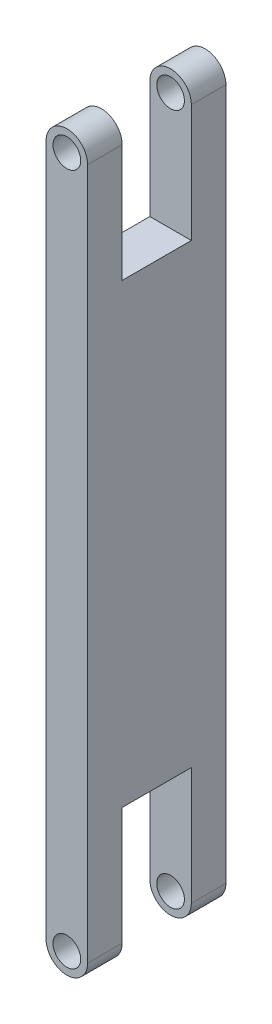
SolidWorks part; units mm, degrees
ref_plane "前视基准面" through (0, 0, 0) normal (0, 0, 1) x (1, 0, 0)
ref_plane "上视基准面" through (0, 0, 0) normal (0, 1, 0) x (1, 0, 0)
ref_plane "右视基准面" through (0, 0, 0) normal (1, 0, 0) x (0, 0, -1)
other "Configuration Table"
sketch "草图1" plane through (0, 0, 0) normal (0, 0, 1) x (1, 0, 0)
  line L0 (0, 0) -> (0, 250) construction
  line L1 (-7.5, 0) -> (-7.5, 250)
  line L2 (7.5, 0) -> (7.5, 250)
  arc A0 (-7.5, 0) -> (7.5, 0) centre (0, 0) ccw
  arc A1 (7.5, 250) -> (-7.5, 250) centre (0, 250) ccw
  point P3 (0, 125)
  dimension "D1" = 7.5
  dimension "D2" = 250
extrude "凸台-拉伸1" add sketch "草图1" along normal blind 50
sketch "草图2" plane through (7.5, 0, 0) normal (1, 0, 0) x (0, 0, -1)
  line L0 (0, 257.5) -> (-50, 257.5) construction
  line L1 (-37.5, 257.5) -> (-12.5, 257.5)
  line L2 (-37.5, 257.5) -> (-37.5, 207.5)
  line L3 (-37.5, 207.5) -> (-12.5, 207.5)
  line L4 (-12.5, 257.5) -> (-12.5, 207.5)
  line L5 (-50, -7.5) -> (0, -7.5) construction
  line L6 (-37.5, -7.5) -> (-12.5, -7.5)
  line L7 (-37.5, -7.5) -> (-37.5, 42.5)
  line L8 (-37.5, 42.5) -> (-12.5, 42.5)
  line L9 (-12.5, -7.5) -> (-12.5, 42.5)
  line L10 (-50, 0) -> (-50, 250) construction
  dimension "D1" = 50
  dimension "D2" = 50
  dimension "D3" = 25
  dimension "D4" = 25
  dimension "D5" = 12.5
extrude "切除-拉伸1" cut sketch "草图2" against normal through all
sketch "草图3" plane through (0, 0, 50) normal (0, 0, 1) x (1, 0, 0)
  circle A0 centre (0, 250) radius 5
  circle A1 centre (0, 0) radius 5
  dimension "D1" = 10
extrude "切除-拉伸2" cut sketch "草图3" against normal through all
